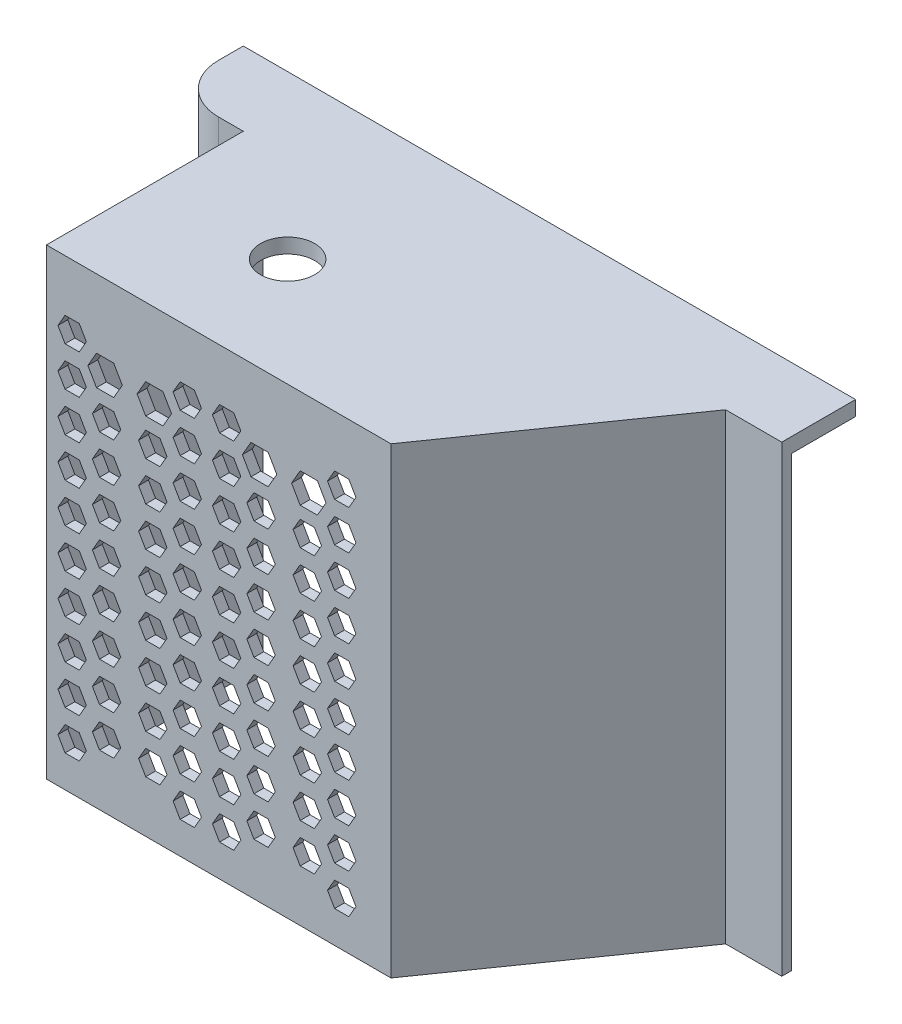
SolidWorks part; units mm, degrees
ref_plane "Ön Düzlem" through (0, 0, 0) normal (0, 0, 1) x (1, 0, 0)
ref_plane "Üst Düzlem" through (0, 0, 0) normal (0, 1, 0) x (1, 0, 0)
ref_plane "Sağ Düzlem" through (0, 0, 0) normal (1, 0, 0) x (0, 0, -1)
sketch "Çizim1" plane through (0, 0, 0) normal (0, 1, 0) x (1, 0, 0)
  line L0 (0, 0) -> (70, 0)
  line L5 (0, 0) -> (0, 30)
  line L8 (0, 30) -> (-3, 30)
  line L9 (-13, 40) -> (-13, 42)
  line L10 (-13, 42) -> (-11, 42)
  line L11 (70, 0) -> (99.4087, 42)
  line L12 (-1, 32) -> (2, 32)
  line L13 (2, 32) -> (2, 2)
  line L14 (2, 2) -> (69, 2)
  line L15 (69, 2) -> (97.0083, 42)
  line L16 (97.0083, 42) -> (99.4087, 42)
  arc A0 (-3, 30) -> (-13, 40) centre (-3, 40) cw
  arc A1 (-11, 42) -> (-1, 32) centre (-1, 42) ccw
  dimension "D3" = 10
  dimension "D1" = 70
  dimension "D2" = 30
extrude "Yükseklik-Ekstrüzyon1" add sketch "Çizim1" along normal blind 91
sketch "Çizim2" plane through (0, 0, 0) normal (0, 0, 1) x (1, 0, 0)
  line L0 (70, 91) -> (60, 91)
  line L1 (0, 91) -> (70, 91) construction
  line L2 (61.4434, 75.5) -> (62.8868, 73)
  line L3 (58.5566, 75.5) -> (61.4434, 75.5)
  line L4 (62.8868, 65) -> (61.4434, 67.5)
  line L5 (57.1132, 73) -> (58.5566, 75.5)
  line L6 (58.5566, 70.5) -> (57.1132, 73)
  line L7 (62.8868, 81) -> (61.4434, 83.5)
  line L8 (61.4434, 83.5) -> (58.5566, 83.5)
  line L9 (58.5566, 83.5) -> (57.1132, 81)
  line L10 (57.1132, 81) -> (58.5566, 78.5)
  line L11 (58.5566, 78.5) -> (61.4434, 78.5)
  line L12 (61.4434, 78.5) -> (62.8868, 81)
  line L13 (61.4434, 70.5) -> (58.5566, 70.5)
  line L14 (62.8868, 73) -> (61.4434, 70.5)
  line L15 (61.4434, 43.5) -> (62.8868, 41)
  line L16 (61.4434, 67.5) -> (58.5566, 67.5)
  line L17 (61.4434, 59.5) -> (62.8868, 57)
  line L18 (58.5566, 59.5) -> (61.4434, 59.5)
  line L19 (57.1132, 57) -> (58.5566, 59.5)
  line L20 (58.5566, 54.5) -> (57.1132, 57)
  line L21 (61.4434, 54.5) -> (58.5566, 54.5)
  line L22 (62.8868, 57) -> (61.4434, 54.5)
  line L23 (58.5566, 67.5) -> (57.1132, 65)
  line L24 (57.1132, 65) -> (58.5566, 62.5)
  line L25 (58.5566, 62.5) -> (61.4434, 62.5)
  line L26 (61.4434, 62.5) -> (62.8868, 65)
  line L27 (61.4434, 11.5) -> (62.8868, 9)
  line L28 (58.5566, 43.5) -> (61.4434, 43.5)
  line L29 (57.1132, 41) -> (58.5566, 43.5)
  line L30 (58.5566, 38.5) -> (57.1132, 41)
  line L31 (62.8868, 49) -> (61.4434, 51.5)
  line L32 (61.4434, 51.5) -> (58.5566, 51.5)
  line L33 (58.5566, 51.5) -> (57.1132, 49)
  line L34 (57.1132, 49) -> (58.5566, 46.5)
  line L35 (58.5566, 46.5) -> (61.4434, 46.5)
  line L36 (61.4434, 46.5) -> (62.8868, 49)
  line L37 (61.4434, 38.5) -> (58.5566, 38.5)
  line L38 (62.8868, 33) -> (61.4434, 35.5)
  line L39 (61.4434, 35.5) -> (58.5566, 35.5)
  line L40 (61.4434, 27.5) -> (62.8868, 25)
  line L41 (58.5566, 27.5) -> (61.4434, 27.5)
  line L42 (57.1132, 25) -> (58.5566, 27.5)
  line L43 (58.5566, 22.5) -> (57.1132, 25)
  line L44 (61.4434, 22.5) -> (58.5566, 22.5)
  line L45 (62.8868, 25) -> (61.4434, 22.5)
  line L46 (58.5566, 35.5) -> (57.1132, 33)
  line L47 (57.1132, 33) -> (58.5566, 30.5)
  line L48 (62.8868, 41) -> (61.4434, 38.5)
  line L49 (58.5566, 30.5) -> (61.4434, 30.5)
  line L50 (61.4434, 30.5) -> (62.8868, 33)
  line L51 (42.1699, 10.5) -> (40.7265, 13)
  line L52 (58.5566, 11.5) -> (61.4434, 11.5)
  line L53 (57.1132, 9) -> (58.5566, 11.5)
  line L54 (58.5566, 6.5) -> (57.1132, 9)
  line L55 (62.8868, 17) -> (61.4434, 19.5)
  line L56 (61.4434, 19.5) -> (58.5566, 19.5)
  line L57 (58.5566, 19.5) -> (57.1132, 17)
  line L58 (57.1132, 17) -> (58.5566, 14.5)
  line L59 (58.5566, 14.5) -> (61.4434, 14.5)
  line L60 (61.4434, 14.5) -> (62.8868, 17)
  line L61 (61.4434, 6.5) -> (58.5566, 6.5)
  line L62 (62.8868, 9) -> (61.4434, 6.5)
  line L63 (54.4434, 71.5) -> (55.8868, 69)
  line L64 (51.5566, 71.5) -> (54.4434, 71.5)
  line L65 (56.8066, 77) -> (55.0566, 80.0311)
  line L66 (55.0566, 80.0311) -> (51.5566, 80.0311)
  line L67 (51.5566, 80.0311) -> (49.8066, 77)
  line L68 (49.8066, 77) -> (51.5566, 73.9689)
  line L69 (51.5566, 73.9689) -> (55.0566, 73.9689)
  line L70 (55.0566, 73.9689) -> (56.8066, 77)
  line L71 (50.1132, 69) -> (51.5566, 71.5)
  line L72 (51.5566, 66.5) -> (50.1132, 69)
  line L73 (54.4434, 66.5) -> (51.5566, 66.5)
  line L74 (55.8868, 69) -> (54.4434, 66.5)
  line L75 (55.8868, 61) -> (54.4434, 63.5)
  line L76 (54.4434, 63.5) -> (51.5566, 63.5)
  line L77 (51.5566, 63.5) -> (50.1132, 61)
  line L78 (50.1132, 61) -> (51.5566, 58.5)
  line L79 (54.4434, 55.5) -> (55.8868, 53)
  line L80 (51.5566, 55.5) -> (54.4434, 55.5)
  line L81 (50.1132, 53) -> (51.5566, 55.5)
  line L82 (51.5566, 50.5) -> (50.1132, 53)
  line L83 (54.4434, 50.5) -> (51.5566, 50.5)
  line L84 (55.8868, 53) -> (54.4434, 50.5)
  line L85 (51.5566, 58.5) -> (54.4434, 58.5)
  line L86 (54.4434, 58.5) -> (55.8868, 61)
  line L87 (54.4434, 39.5) -> (55.8868, 37)
  line L88 (51.5566, 39.5) -> (54.4434, 39.5)
  line L89 (55.8868, 45) -> (54.4434, 47.5)
  line L90 (54.4434, 47.5) -> (51.5566, 47.5)
  line L91 (51.5566, 47.5) -> (50.1132, 45)
  line L92 (50.1132, 45) -> (51.5566, 42.5)
  line L93 (51.5566, 42.5) -> (54.4434, 42.5)
  line L94 (54.4434, 42.5) -> (55.8868, 45)
  line L95 (50.1132, 37) -> (51.5566, 39.5)
  line L96 (51.5566, 34.5) -> (50.1132, 37)
  line L97 (54.4434, 34.5) -> (51.5566, 34.5)
  line L98 (55.8868, 37) -> (54.4434, 34.5)
  line L99 (55.8868, 29) -> (54.4434, 31.5)
  line L100 (54.4434, 31.5) -> (51.5566, 31.5)
  line L101 (51.5566, 31.5) -> (50.1132, 29)
  line L102 (50.1132, 29) -> (51.5566, 26.5)
  line L103 (54.4434, 23.5) -> (55.8868, 21)
  line L104 (51.5566, 23.5) -> (54.4434, 23.5)
  line L105 (50.1132, 21) -> (51.5566, 23.5)
  line L106 (51.5566, 18.5) -> (50.1132, 21)
  line L107 (54.4434, 18.5) -> (51.5566, 18.5)
  line L108 (55.8868, 21) -> (54.4434, 18.5)
  line L109 (51.5566, 26.5) -> (54.4434, 26.5)
  line L110 (54.4434, 26.5) -> (55.8868, 29)
  line L111 (55.8868, 13) -> (54.4434, 15.5)
  line L112 (54.4434, 15.5) -> (51.5566, 15.5)
  line L113 (51.5566, 15.5) -> (50.1132, 13)
  line L114 (50.1132, 13) -> (51.5566, 10.5)
  line L115 (51.5566, 10.5) -> (54.4434, 10.5)
  line L116 (54.4434, 10.5) -> (55.8868, 13)
  line L117 (30.0566, 75.5) -> (31.5, 73)
  line L118 (45.0566, 10.5) -> (42.1699, 10.5)
  line L119 (46.5, 13) -> (45.0566, 10.5)
  line L120 (45.0566, 15.5) -> (46.5, 13)
  line L121 (42.1699, 15.5) -> (45.0566, 15.5)
  line L122 (40.7265, 13) -> (42.1699, 15.5)
  line L123 (42.1699, 26.5) -> (40.7265, 29)
  line L124 (45.0566, 26.5) -> (42.1699, 26.5)
  line L125 (40.7265, 21) -> (42.1699, 18.5)
  line L126 (42.1699, 18.5) -> (45.0566, 18.5)
  line L127 (45.0566, 18.5) -> (46.5, 21)
  line L128 (46.5, 21) -> (45.0566, 23.5)
  line L129 (45.0566, 23.5) -> (42.1699, 23.5)
  line L130 (42.1699, 23.5) -> (40.7265, 21)
  line L131 (46.5, 29) -> (45.0566, 26.5)
  line L132 (45.0566, 31.5) -> (46.5, 29)
  line L133 (42.1699, 31.5) -> (45.0566, 31.5)
  line L134 (40.7265, 29) -> (42.1699, 31.5)
  line L135 (40.7265, 37) -> (42.1699, 34.5)
  line L136 (42.1699, 34.5) -> (45.0566, 34.5)
  line L137 (45.0566, 34.5) -> (46.5, 37)
  line L138 (46.5, 37) -> (45.0566, 39.5)
  line L139 (42.1699, 42.5) -> (40.7265, 45)
  line L140 (45.0566, 42.5) -> (42.1699, 42.5)
  line L141 (46.5, 45) -> (45.0566, 42.5)
  line L142 (45.0566, 47.5) -> (46.5, 45)
  line L143 (42.1699, 47.5) -> (45.0566, 47.5)
  line L144 (40.7265, 45) -> (42.1699, 47.5)
  line L145 (45.0566, 39.5) -> (42.1699, 39.5)
  line L146 (42.1699, 39.5) -> (40.7265, 37)
  line L147 (42.1699, 58.5) -> (40.7265, 61)
  line L148 (45.0566, 58.5) -> (42.1699, 58.5)
  line L149 (40.7265, 53) -> (42.1699, 50.5)
  line L150 (42.1699, 50.5) -> (45.0566, 50.5)
  line L151 (45.0566, 50.5) -> (46.5, 53)
  line L152 (46.5, 53) -> (45.0566, 55.5)
  line L153 (45.0566, 55.5) -> (42.1699, 55.5)
  line L154 (42.1699, 55.5) -> (40.7265, 53)
  line L155 (46.5, 61) -> (45.0566, 58.5)
  line L156 (45.0566, 63.5) -> (46.5, 61)
  line L157 (42.1699, 63.5) -> (45.0566, 63.5)
  line L158 (40.7265, 61) -> (42.1699, 63.5)
  line L159 (40.7265, 69) -> (42.1699, 66.5)
  line L160 (42.1699, 66.5) -> (45.0566, 66.5)
  line L161 (45.0566, 66.5) -> (46.5, 69)
  line L162 (46.5, 69) -> (45.0566, 71.5)
  line L163 (41.5566, 73.9689) -> (39.8066, 77)
  line L164 (45.0566, 73.9689) -> (41.5566, 73.9689)
  line L165 (46.8066, 77) -> (45.0566, 73.9689)
  line L166 (45.0566, 80.0311) -> (46.8066, 77)
  line L167 (41.5566, 80.0311) -> (45.0566, 80.0311)
  line L168 (39.8066, 77) -> (41.5566, 80.0311)
  line L169 (45.0566, 71.5) -> (42.1699, 71.5)
  line L170 (42.1699, 71.5) -> (40.7265, 69)
  line L171 (33.7265, 9) -> (35.1699, 6.5)
  line L172 (35.1699, 6.5) -> (38.0566, 6.5)
  line L173 (35.1699, 14.5) -> (33.7265, 17)
  line L174 (38.0566, 14.5) -> (35.1699, 14.5)
  line L175 (39.5, 17) -> (38.0566, 14.5)
  line L176 (38.0566, 19.5) -> (39.5, 17)
  line L177 (35.1699, 19.5) -> (38.0566, 19.5)
  line L178 (33.7265, 17) -> (35.1699, 19.5)
  line L179 (38.0566, 6.5) -> (39.5, 9)
  line L180 (39.5, 9) -> (38.0566, 11.5)
  line L181 (38.0566, 11.5) -> (35.1699, 11.5)
  line L182 (35.1699, 30.5) -> (33.7265, 33)
  line L183 (38.0566, 30.5) -> (35.1699, 30.5)
  line L184 (33.7265, 41) -> (35.1699, 38.5)
  line L185 (39.5, 33) -> (38.0566, 30.5)
  line L186 (38.0566, 35.5) -> (39.5, 33)
  line L187 (33.7265, 25) -> (35.1699, 22.5)
  line L188 (35.1699, 22.5) -> (38.0566, 22.5)
  line L189 (38.0566, 22.5) -> (39.5, 25)
  line L190 (39.5, 25) -> (38.0566, 27.5)
  line L191 (38.0566, 27.5) -> (35.1699, 27.5)
  line L192 (35.1699, 27.5) -> (33.7265, 25)
  line L193 (35.1699, 35.5) -> (38.0566, 35.5)
  line L194 (33.7265, 33) -> (35.1699, 35.5)
  line L195 (35.1699, 38.5) -> (38.0566, 38.5)
  line L196 (35.1699, 46.5) -> (33.7265, 49)
  line L197 (38.0566, 46.5) -> (35.1699, 46.5)
  line L198 (39.5, 49) -> (38.0566, 46.5)
  line L199 (38.0566, 51.5) -> (39.5, 49)
  line L200 (35.1699, 51.5) -> (38.0566, 51.5)
  line L201 (33.7265, 49) -> (35.1699, 51.5)
  line L202 (38.0566, 38.5) -> (39.5, 41)
  line L203 (39.5, 41) -> (38.0566, 43.5)
  line L204 (38.0566, 43.5) -> (35.1699, 43.5)
  line L205 (35.1699, 11.5) -> (33.7265, 9)
  line L206 (35.1699, 62.5) -> (33.7265, 65)
  line L207 (38.0566, 62.5) -> (35.1699, 62.5)
  line L208 (39.5, 65) -> (38.0566, 62.5)
  line L209 (38.0566, 67.5) -> (39.5, 65)
  line L210 (33.7265, 57) -> (35.1699, 54.5)
  line L211 (35.1699, 54.5) -> (38.0566, 54.5)
  line L212 (38.0566, 54.5) -> (39.5, 57)
  line L213 (39.5, 57) -> (38.0566, 59.5)
  line L214 (38.0566, 59.5) -> (35.1699, 59.5)
  line L215 (35.1699, 59.5) -> (33.7265, 57)
  line L216 (35.1699, 67.5) -> (38.0566, 67.5)
  line L217 (35.1699, 43.5) -> (33.7265, 41)
  line L218 (33.7265, 73) -> (35.1699, 70.5)
  line L219 (35.1699, 70.5) -> (38.0566, 70.5)
  line L220 (35.1699, 78.5) -> (33.7265, 81)
  line L221 (38.0566, 78.5) -> (35.1699, 78.5)
  line L222 (39.5, 81) -> (38.0566, 78.5)
  line L223 (38.0566, 83.5) -> (39.5, 81)
  line L224 (35.1699, 83.5) -> (38.0566, 83.5)
  line L225 (33.7265, 81) -> (35.1699, 83.5)
  line L226 (38.0566, 70.5) -> (39.5, 73)
  line L227 (39.5, 73) -> (38.0566, 75.5)
  line L228 (33.7265, 65) -> (35.1699, 67.5)
  line L229 (38.0566, 75.5) -> (35.1699, 75.5)
  line L230 (35.1699, 75.5) -> (33.7265, 73)
  line L232 (27.1699, 75.5) -> (30.0566, 75.5)
  line L233 (31.5, 65) -> (30.0566, 67.5)
  line L234 (25.7265, 73) -> (27.1699, 75.5)
  line L235 (27.1699, 70.5) -> (25.7265, 73)
  line L236 (31.5, 81) -> (30.0566, 83.5)
  line L237 (30.0566, 83.5) -> (27.1699, 83.5)
  line L238 (27.1699, 83.5) -> (25.7265, 81)
  line L239 (25.7265, 81) -> (27.1699, 78.5)
  line L240 (27.1699, 78.5) -> (30.0566, 78.5)
  line L241 (30.0566, 78.5) -> (31.5, 81)
  line L242 (30.0566, 70.5) -> (27.1699, 70.5)
  line L243 (31.5, 73) -> (30.0566, 70.5)
  line L244 (30.0566, 43.5) -> (31.5, 41)
  line L245 (30.0566, 67.5) -> (27.1699, 67.5)
  line L246 (30.0566, 59.5) -> (31.5, 57)
  line L247 (27.1699, 59.5) -> (30.0566, 59.5)
  line L248 (25.7265, 57) -> (27.1699, 59.5)
  line L249 (27.1699, 54.5) -> (25.7265, 57)
  line L250 (30.0566, 54.5) -> (27.1699, 54.5)
  line L251 (31.5, 57) -> (30.0566, 54.5)
  line L252 (27.1699, 67.5) -> (25.7265, 65)
  line L253 (25.7265, 65) -> (27.1699, 62.5)
  line L254 (27.1699, 62.5) -> (30.0566, 62.5)
  line L255 (30.0566, 62.5) -> (31.5, 65)
  line L256 (30.0566, 11.5) -> (31.5, 9)
  line L257 (27.1699, 43.5) -> (30.0566, 43.5)
  line L258 (25.7265, 41) -> (27.1699, 43.5)
  line L259 (27.1699, 38.5) -> (25.7265, 41)
  line L260 (31.5, 49) -> (30.0566, 51.5)
  line L261 (30.0566, 51.5) -> (27.1699, 51.5)
  line L262 (27.1699, 51.5) -> (25.7265, 49)
  line L263 (25.7265, 49) -> (27.1699, 46.5)
  line L264 (27.1699, 46.5) -> (30.0566, 46.5)
  line L265 (30.0566, 46.5) -> (31.5, 49)
  line L266 (30.0566, 38.5) -> (27.1699, 38.5)
  line L267 (31.5, 33) -> (30.0566, 35.5)
  line L268 (30.0566, 35.5) -> (27.1699, 35.5)
  line L269 (30.0566, 27.5) -> (31.5, 25)
  line L270 (27.1699, 27.5) -> (30.0566, 27.5)
  line L271 (25.7265, 25) -> (27.1699, 27.5)
  line L272 (27.1699, 22.5) -> (25.7265, 25)
  line L273 (30.0566, 22.5) -> (27.1699, 22.5)
  line L274 (31.5, 25) -> (30.0566, 22.5)
  line L275 (27.1699, 35.5) -> (25.7265, 33)
  line L276 (25.7265, 33) -> (27.1699, 30.5)
  line L277 (31.5, 41) -> (30.0566, 38.5)
  line L278 (27.1699, 30.5) -> (30.0566, 30.5)
  line L279 (30.0566, 30.5) -> (31.5, 33)
  line L280 (27.1699, 11.5) -> (30.0566, 11.5)
  line L281 (25.7265, 9) -> (27.1699, 11.5)
  line L282 (27.1699, 6.5) -> (25.7265, 9)
  line L283 (31.5, 17) -> (30.0566, 19.5)
  line L284 (30.0566, 19.5) -> (27.1699, 19.5)
  line L285 (27.1699, 19.5) -> (25.7265, 17)
  line L286 (25.7265, 17) -> (27.1699, 14.5)
  line L287 (27.1699, 14.5) -> (30.0566, 14.5)
  line L288 (30.0566, 14.5) -> (31.5, 17)
  line L289 (30.0566, 6.5) -> (27.1699, 6.5)
  line L290 (31.5, 9) -> (30.0566, 6.5)
  line L291 (23.0566, 71.5) -> (24.5, 69)
  line L292 (20.1699, 71.5) -> (23.0566, 71.5)
  line L293 (25.4199, 77) -> (23.6699, 80.0311)
  line L294 (23.6699, 80.0311) -> (20.1699, 80.0311)
  line L295 (20.1699, 80.0311) -> (18.4199, 77)
  line L296 (18.4199, 77) -> (20.1699, 73.9689)
  line L297 (20.1699, 73.9689) -> (23.6699, 73.9689)
  line L298 (23.6699, 73.9689) -> (25.4199, 77)
  line L299 (18.7265, 69) -> (20.1699, 71.5)
  line L300 (20.1699, 66.5) -> (18.7265, 69)
  line L301 (23.0566, 66.5) -> (20.1699, 66.5)
  line L302 (24.5, 69) -> (23.0566, 66.5)
  line L303 (24.5, 61) -> (23.0566, 63.5)
  line L304 (23.0566, 63.5) -> (20.1699, 63.5)
  line L305 (20.1699, 63.5) -> (18.7265, 61)
  line L306 (18.7265, 61) -> (20.1699, 58.5)
  line L307 (23.0566, 55.5) -> (24.5, 53)
  line L308 (20.1699, 55.5) -> (23.0566, 55.5)
  line L309 (18.7265, 53) -> (20.1699, 55.5)
  line L310 (20.1699, 50.5) -> (18.7265, 53)
  line L311 (23.0566, 50.5) -> (20.1699, 50.5)
  line L312 (24.5, 53) -> (23.0566, 50.5)
  line L313 (20.1699, 58.5) -> (23.0566, 58.5)
  line L314 (23.0566, 58.5) -> (24.5, 61)
  line L315 (23.0566, 39.5) -> (24.5, 37)
  line L316 (20.1699, 39.5) -> (23.0566, 39.5)
  line L317 (24.5, 45) -> (23.0566, 47.5)
  line L318 (23.0566, 47.5) -> (20.1699, 47.5)
  line L319 (20.1699, 47.5) -> (18.7265, 45)
  line L320 (18.7265, 45) -> (20.1699, 42.5)
  line L321 (20.1699, 42.5) -> (23.0566, 42.5)
  line L322 (23.0566, 42.5) -> (24.5, 45)
  line L323 (18.7265, 37) -> (20.1699, 39.5)
  line L324 (20.1699, 34.5) -> (18.7265, 37)
  line L325 (23.0566, 34.5) -> (20.1699, 34.5)
  line L326 (24.5, 37) -> (23.0566, 34.5)
  line L327 (24.5, 29) -> (23.0566, 31.5)
  line L328 (23.0566, 31.5) -> (20.1699, 31.5)
  line L329 (20.1699, 31.5) -> (18.7265, 29)
  line L330 (18.7265, 29) -> (20.1699, 26.5)
  line L331 (23.0566, 23.5) -> (24.5, 21)
  line L332 (20.1699, 23.5) -> (23.0566, 23.5)
  line L333 (18.7265, 21) -> (20.1699, 23.5)
  line L334 (20.1699, 18.5) -> (18.7265, 21)
  line L335 (23.0566, 18.5) -> (20.1699, 18.5)
  line L336 (24.5, 21) -> (23.0566, 18.5)
  line L337 (20.1699, 26.5) -> (23.0566, 26.5)
  line L338 (23.0566, 26.5) -> (24.5, 29)
  line L339 (24.5, 13) -> (23.0566, 15.5)
  line L340 (23.0566, 15.5) -> (20.1699, 15.5)
  line L341 (20.1699, 15.5) -> (18.7265, 13)
  line L342 (18.7265, 13) -> (20.1699, 10.5)
  line L343 (20.1699, 10.5) -> (23.0566, 10.5)
  line L344 (10.7831, 10.5) -> (9.3397, 13)
  line L345 (13.6699, 10.5) -> (10.7831, 10.5)
  line L346 (15.1132, 13) -> (13.6699, 10.5)
  line L347 (13.6699, 15.5) -> (15.1132, 13)
  line L348 (10.7831, 15.5) -> (13.6699, 15.5)
  line L349 (9.3397, 13) -> (10.7831, 15.5)
  line L350 (10.7831, 26.5) -> (9.3397, 29)
  line L351 (13.6699, 26.5) -> (10.7831, 26.5)
  line L352 (9.3397, 21) -> (10.7831, 18.5)
  line L353 (10.7831, 18.5) -> (13.6699, 18.5)
  line L354 (13.6699, 18.5) -> (15.1132, 21)
  line L355 (15.1132, 21) -> (13.6699, 23.5)
  line L356 (13.6699, 23.5) -> (10.7831, 23.5)
  line L357 (10.7831, 23.5) -> (9.3397, 21)
  line L358 (15.1132, 29) -> (13.6699, 26.5)
  line L359 (13.6699, 31.5) -> (15.1132, 29)
  line L360 (10.7831, 31.5) -> (13.6699, 31.5)
  line L361 (9.3397, 29) -> (10.7831, 31.5)
  line L362 (9.3397, 37) -> (10.7831, 34.5)
  line L363 (10.7831, 34.5) -> (13.6699, 34.5)
  line L364 (13.6699, 34.5) -> (15.1132, 37)
  line L365 (15.1132, 37) -> (13.6699, 39.5)
  line L366 (10.7831, 42.5) -> (9.3397, 45)
  line L367 (13.6699, 42.5) -> (10.7831, 42.5)
  line L368 (15.1132, 45) -> (13.6699, 42.5)
  line L369 (13.6699, 47.5) -> (15.1132, 45)
  line L370 (10.7831, 47.5) -> (13.6699, 47.5)
  line L371 (9.3397, 45) -> (10.7831, 47.5)
  line L372 (13.6699, 39.5) -> (10.7831, 39.5)
  line L373 (10.7831, 39.5) -> (9.3397, 37)
  line L374 (10.7831, 58.5) -> (9.3397, 61)
  line L375 (13.6699, 58.5) -> (10.7831, 58.5)
  line L376 (9.3397, 53) -> (10.7831, 50.5)
  line L377 (10.7831, 50.5) -> (13.6699, 50.5)
  line L378 (13.6699, 50.5) -> (15.1132, 53)
  line L379 (15.1132, 53) -> (13.6699, 55.5)
  line L380 (13.6699, 55.5) -> (10.7831, 55.5)
  line L381 (10.7831, 55.5) -> (9.3397, 53)
  line L382 (15.1132, 61) -> (13.6699, 58.5)
  line L383 (13.6699, 63.5) -> (15.1132, 61)
  line L384 (10.7831, 63.5) -> (13.6699, 63.5)
  line L385 (9.3397, 61) -> (10.7831, 63.5)
  line L386 (9.3397, 69) -> (10.7831, 66.5)
  line L387 (10.7831, 66.5) -> (13.6699, 66.5)
  line L388 (13.6699, 66.5) -> (15.1132, 69)
  line L389 (15.1132, 69) -> (13.6699, 71.5)
  line L390 (10.1699, 73.9689) -> (8.4199, 77)
  line L391 (13.6699, 73.9689) -> (10.1699, 73.9689)
  line L392 (15.4199, 77) -> (13.6699, 73.9689)
  line L393 (13.6699, 80.0311) -> (15.4199, 77)
  line L394 (10.1699, 80.0311) -> (13.6699, 80.0311)
  line L395 (8.4199, 77) -> (10.1699, 80.0311)
  line L396 (13.6699, 71.5) -> (10.7831, 71.5)
  line L397 (10.7831, 71.5) -> (9.3397, 69)
  line L398 (2.3397, 9) -> (3.7831, 6.5)
  line L399 (3.7831, 6.5) -> (6.6699, 6.5)
  line L400 (3.7831, 14.5) -> (2.3397, 17)
  line L401 (6.6699, 14.5) -> (3.7831, 14.5)
  line L402 (8.1132, 17) -> (6.6699, 14.5)
  line L403 (6.6699, 19.5) -> (8.1132, 17)
  line L404 (3.7831, 19.5) -> (6.6699, 19.5)
  line L405 (2.3397, 17) -> (3.7831, 19.5)
  line L406 (6.6699, 6.5) -> (8.1132, 9)
  line L407 (8.1132, 9) -> (6.6699, 11.5)
  line L408 (6.6699, 11.5) -> (3.7831, 11.5)
  line L409 (23.0566, 10.5) -> (24.5, 13)
  line L410 (3.7831, 30.5) -> (2.3397, 33)
  line L411 (6.6699, 30.5) -> (3.7831, 30.5)
  line L412 (2.3397, 41) -> (3.7831, 38.5)
  line L413 (8.1132, 33) -> (6.6699, 30.5)
  line L414 (6.6699, 35.5) -> (8.1132, 33)
  line L415 (2.3397, 25) -> (3.7831, 22.5)
  line L416 (3.7831, 22.5) -> (6.6699, 22.5)
  line L417 (6.6699, 22.5) -> (8.1132, 25)
  line L418 (8.1132, 25) -> (6.6699, 27.5)
  line L419 (6.6699, 27.5) -> (3.7831, 27.5)
  line L420 (3.7831, 27.5) -> (2.3397, 25)
  line L421 (3.7831, 35.5) -> (6.6699, 35.5)
  line L422 (2.3397, 33) -> (3.7831, 35.5)
  line L423 (3.7831, 38.5) -> (6.6699, 38.5)
  line L424 (3.7831, 46.5) -> (2.3397, 49)
  line L425 (6.6699, 46.5) -> (3.7831, 46.5)
  line L426 (8.1132, 49) -> (6.6699, 46.5)
  line L427 (6.6699, 51.5) -> (8.1132, 49)
  line L428 (3.7831, 51.5) -> (6.6699, 51.5)
  line L429 (2.3397, 49) -> (3.7831, 51.5)
  line L430 (6.6699, 38.5) -> (8.1132, 41)
  line L431 (8.1132, 41) -> (6.6699, 43.5)
  line L432 (6.6699, 43.5) -> (3.7831, 43.5)
  line L433 (3.7831, 11.5) -> (2.3397, 9)
  line L434 (3.7831, 62.5) -> (2.3397, 65)
  line L435 (6.6699, 62.5) -> (3.7831, 62.5)
  line L436 (8.1132, 65) -> (6.6699, 62.5)
  line L437 (6.6699, 67.5) -> (8.1132, 65)
  line L438 (2.3397, 57) -> (3.7831, 54.5)
  line L439 (3.7831, 54.5) -> (6.6699, 54.5)
  line L440 (6.6699, 54.5) -> (8.1132, 57)
  line L441 (8.1132, 57) -> (6.6699, 59.5)
  line L442 (6.6699, 59.5) -> (3.7831, 59.5)
  line L443 (3.7831, 59.5) -> (2.3397, 57)
  line L444 (3.7831, 67.5) -> (6.6699, 67.5)
  line L445 (3.7831, 43.5) -> (2.3397, 41)
  line L446 (2.3397, 73) -> (3.7831, 70.5)
  line L447 (3.7831, 70.5) -> (6.6699, 70.5)
  line L448 (3.7831, 78.5) -> (2.3397, 81)
  line L449 (6.6699, 78.5) -> (3.7831, 78.5)
  line L450 (8.1132, 81) -> (6.6699, 78.5)
  line L451 (6.6699, 83.5) -> (8.1132, 81)
  line L452 (3.7831, 83.5) -> (6.6699, 83.5)
  line L453 (2.3397, 81) -> (3.7831, 83.5)
  line L454 (6.6699, 70.5) -> (8.1132, 73)
  line L455 (8.1132, 73) -> (6.6699, 75.5)
  line L456 (2.3397, 65) -> (3.7831, 67.5)
  line L457 (6.6699, 75.5) -> (3.7831, 75.5)
  line L458 (3.7831, 75.5) -> (2.3397, 73)
  circle A0 centre (60, 81) radius 2.5 construction
  circle A1 centre (60, 73) radius 2.5 construction
  circle A2 centre (60, 65) radius 2.5 construction
  circle A3 centre (60, 57) radius 2.5 construction
  circle A4 centre (60, 49) radius 2.5 construction
  circle A5 centre (60, 41) radius 2.5 construction
  circle A6 centre (60, 33) radius 2.5 construction
  circle A7 centre (60, 25) radius 2.5 construction
  circle A8 centre (60, 17) radius 2.5 construction
  circle A9 centre (60, 9) radius 2.5 construction
  circle A10 centre (53.3066, 77) radius 3.0311 construction
  circle A11 centre (53, 69) radius 2.5 construction
  circle A12 centre (53, 61) radius 2.5 construction
  circle A13 centre (53, 53) radius 2.5 construction
  circle A14 centre (53, 45) radius 2.5 construction
  circle A15 centre (53, 37) radius 2.5 construction
  circle A16 centre (53, 29) radius 2.5 construction
  circle A17 centre (53, 21) radius 2.5 construction
  circle A18 centre (53, 13) radius 2.5 construction
  circle A19 centre (43.6132, 13) radius 2.5 construction
  circle A20 centre (43.6132, 21) radius 2.5 construction
  circle A21 centre (43.6132, 29) radius 2.5 construction
  circle A22 centre (43.6132, 37) radius 2.5 construction
  circle A23 centre (43.6132, 45) radius 2.5 construction
  circle A24 centre (43.6132, 53) radius 2.5 construction
  circle A25 centre (43.6132, 61) radius 2.5 construction
  circle A26 centre (43.6132, 69) radius 2.5 construction
  circle A27 centre (43.3066, 77) radius 3.0311 construction
  circle A28 centre (36.6132, 9) radius 2.5 construction
  circle A29 centre (36.6132, 17) radius 2.5 construction
  circle A30 centre (36.6132, 25) radius 2.5 construction
  circle A31 centre (36.6132, 33) radius 2.5 construction
  circle A32 centre (36.6132, 41) radius 2.5 construction
  circle A33 centre (36.6132, 49) radius 2.5 construction
  circle A34 centre (36.6132, 57) radius 2.5 construction
  circle A35 centre (36.6132, 65) radius 2.5 construction
  circle A36 centre (36.6132, 73) radius 2.5 construction
  circle A37 centre (36.6132, 81) radius 2.5 construction
  circle A38 centre (28.6132, 81) radius 2.5 construction
  circle A39 centre (28.6132, 73) radius 2.5 construction
  circle A40 centre (28.6132, 65) radius 2.5 construction
  circle A41 centre (28.6132, 57) radius 2.5 construction
  circle A42 centre (28.6132, 49) radius 2.5 construction
  circle A43 centre (28.6132, 41) radius 2.5 construction
  circle A44 centre (28.6132, 33) radius 2.5 construction
  circle A45 centre (28.6132, 25) radius 2.5 construction
  circle A46 centre (28.6132, 17) radius 2.5 construction
  circle A47 centre (28.6132, 9) radius 2.5 construction
  circle A48 centre (21.9199, 77) radius 3.0311 construction
  circle A49 centre (21.6132, 69) radius 2.5 construction
  circle A50 centre (21.6132, 61) radius 2.5 construction
  circle A51 centre (21.6132, 53) radius 2.5 construction
  circle A52 centre (21.6132, 45) radius 2.5 construction
  circle A53 centre (21.6132, 37) radius 2.5 construction
  circle A54 centre (21.6132, 29) radius 2.5 construction
  circle A55 centre (21.6132, 21) radius 2.5 construction
  circle A56 centre (21.6132, 13) radius 2.5 construction
  circle A57 centre (12.2265, 13) radius 2.5 construction
  circle A58 centre (12.2265, 21) radius 2.5 construction
  circle A59 centre (12.2265, 29) radius 2.5 construction
  circle A60 centre (12.2265, 37) radius 2.5 construction
  circle A61 centre (12.2265, 45) radius 2.5 construction
  circle A62 centre (12.2265, 53) radius 2.5 construction
  circle A63 centre (12.2265, 61) radius 2.5 construction
  circle A64 centre (12.2265, 69) radius 2.5 construction
  circle A65 centre (11.9199, 77) radius 3.0311 construction
  circle A66 centre (5.2265, 9) radius 2.5 construction
  circle A67 centre (5.2265, 17) radius 2.5 construction
  circle A68 centre (5.2265, 25) radius 2.5 construction
  circle A69 centre (5.2265, 33) radius 2.5 construction
  circle A70 centre (5.2265, 41) radius 2.5 construction
  circle A71 centre (5.2265, 49) radius 2.5 construction
  circle A72 centre (5.2265, 57) radius 2.5 construction
  circle A73 centre (5.2265, 65) radius 2.5 construction
  circle A74 centre (5.2265, 73) radius 2.5 construction
  circle A75 centre (5.2265, 81) radius 2.5 construction
extrude "Kes-Ekstrüzyon1" cut sketch "Çizim2" against normal blind 5 contours L408 L433 L398 L399 L406 L407 | L349 L348 L347 L346 L345 L344 | L402 L401 L400 L405 L404 L403 | L417 L418 L419 L420 L415 L416 | L357 L352 L353 L354 L355 L356 | L334 L333 L332 L331 L336 L335 | L340 L341 L342 L343 L409 L339 | L286 L287 L288 L283 L284 L285 | L173 L178 L177 L176 L175 L174 | L280 L256 L290 L289 L282 L281 | L171 L172 L179 L180 L181 L205 | L51 L122 L121 L120 L119 L118 | L126 L127 L128 L129 L130 L125 | L106 L105 L104 L103 L108 L107 | L113 L114 L115 L116 L111 L112 | L58 L59 L60 L55 L56 L57 | L53 L52 L27 L62 L61 L54 | L44 L43 L42 L41 L40 L45 | L110 L99 L100 L101 L102 L109 | L131 L124 L123 L134 L133 L132 | L189 L190 L191 L192 L187 L188 | L274 L273 L272 L271 L270 L269 | L338 L327 L328 L329 L330 L337 | L358 L351 L350 L361 L360 L359 | L413 L411 L410 L422 L421 L414 | L363 L364 L365 L372 L373 L362 | L325 L324 L323 L316 L315 L326 | L278 L279 L267 L268 L275 L276 | L183 L182 L194 L193 L186 L185 | L136 L137 L138 L145 L146 L135 | L97 L96 L95 L88 L87 L98 | L49 L50 L38 L39 L46 L47 | L430 L431 L432 L445 L412 L423 | L367 L366 L371 L370 L369 L368 | L426 L425 L424 L429 L428 L427 | L377 L378 L379 L380 L381 L376 | L440 L441 L442 L443 L438 L439 | L375 L374 L385 L384 L383 L382 | L436 L435 L434 L456 L444 L437 | L387 L388 L389 L396 L397 L386 | L454 L455 L457 L458 L446 L447 | L391 L390 L395 L394 L393 L392 | L450 L449 L448 L453 L452 L451 | L297 L298 L293 L294 L295 L296 | L301 L300 L299 L292 L291 L302 | L313 L314 L303 L304 L305 L306 | L308 L307 L312 L311 L310 L309 | L318 L319 L320 L321 L322 L317 | L257 L244 L277 L266 L259 L258 | L204 L217 L184 L195 L202 L203 | L37 L30 L29 L28 L15 L48 | L35 L36 L31 L32 L33 L34 | L93 L94 L89 L90 L91 L92 | L140 L139 L144 L143 L142 L141 | L197 L196 L201 L200 L199 L198 | L264 L265 L260 L261 L262 L263 | L250 L249 L248 L247 L246 L251 | L83 L82 L81 L80 L79 L84 | L150 L151 L152 L153 L154 L149 | L211 L212 L213 L214 L215 L210 | L148 L147 L158 L157 L156 L155 | L85 L86 L75 L76 L77 L78 | L21 L20 L19 L18 L17 L22 | L25 L26 L4 L16 L23 L24 | L73 L72 L71 L64 L63 L74 | L160 L161 L162 L169 L170 L159 | L207 L206 L228 L216 L209 L208 | L254 L255 L233 L245 L252 L253 | L242 L235 L234 L232 L117 L243 | L240 L241 L236 L237 L238 L239 | L221 L220 L225 L224 L223 L222 | L219 L226 L227 L229 L230 L218 | L164 L163 L168 L167 L166 L165 | L69 L70 L65 L66 L67 L68 | L13 L6 L5 L3 L2 L14 | L11 L12 L7 L8 L9 L10
sketch "Çizim3" plane through (0, 0, 0) normal (0, 1, 0) x (1, 0, 0)
  line L0 (99.4087, 42) -> (109.4087, 42)
  line L1 (109.4087, 42) -> (109.4087, 40)
  line L2 (109.4087, 40) -> (98.0083, 40)
  line L3 (70, 0) -> (99.4087, 42) construction
  line L4 (98.0083, 40) -> (99.4087, 42)
extrude "Yükseklik-Ekstrüzyon2" add sketch "Çizim3" along normal blind 91
sketch "Çizim8" plane through (0, 91, 0) normal (0, 1, 0) x (1, 0, 0)
  line L0 (0, 30) -> (5.7676, 30)
  line L1 (5.7676, 30) -> (5.7676, 46.9805)
  line L2 (5.7676, 46.9805) -> (-19.6704, 46.9805)
  line L3 (-19.6704, 46.9805) -> (-19.6704, 30)
  line L4 (-19.6704, 30) -> (0, 30)
extrude "Kes-Ekstrüzyon4" cut sketch "Çizim8" against normal blind 95
sketch "Çizim9" plane through (0, 91, 0) normal (0, 1, 0) x (1, 0, 0)
  line L0 (0, 30) -> (0, 40)
  line L3 (2, 30) -> (0, 30)
  line L4 (0, 40) -> (-5, 40)
  line L5 (-15, 50) -> (-15, 55)
  line L6 (-15, 55) -> (-13, 55)
  line L7 (-13, 55) -> (-13, 52)
  line L8 (-3, 42) -> (2, 42)
  line L9 (2, 42) -> (2, 30)
  arc A0 (-5, 40) -> (-15, 50) centre (-5, 50) cw
  arc A1 (-13, 52) -> (-3, 42) centre (-3, 52) ccw
  dimension "D1" = 10
extrude "Yükseklik-Ekstrüzyon5" add sketch "Çizim9" against normal blind 91
sketch "Çizim10" plane through (0, 91, 0) normal (0, 1, 0) x (1, 0, 0)
  line L0 (109.4087, 40) -> (109.4087, 55)
  line L1 (109.4087, 55) -> (-15, 55)
  line L2 (-15, 55) -> (-15, 50)
  line L3 (-5, 40) -> (0, 40)
  line L4 (0, 40) -> (0, 0)
  line L5 (0, 0) -> (70, 0)
  line L6 (70, 0) -> (98.0083, 40)
  line L7 (98.0083, 40) -> (109.4087, 40)
  arc A0 (-15, 50) -> (-5, 40) centre (-5, 50) ccw
  dimension "D1" = 10
extrude "Yükseklik-Ekstrüzyon6" add sketch "Çizim10" along normal blind 3
sketch "Çizim11" plane through (0, 91, 0) normal (0, -1, 0) x (1, 0, 0)
  circle A0 centre (27, -22) radius 5.5
extrude "Kes-Ekstrüzyon5" cut sketch "Çizim11" against normal blind 3
